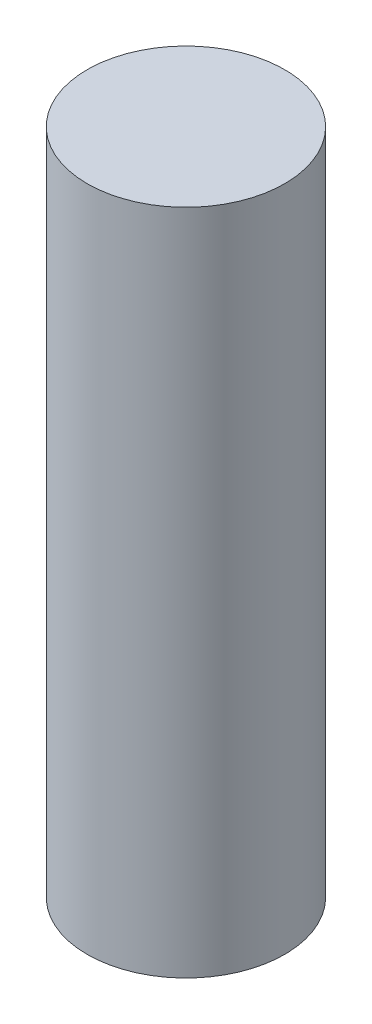
SolidWorks part; units mm, degrees
ref_plane "Front Plane" through (0, 0, 0) normal (0, 0, 1) x (1, 0, 0)
ref_plane "Top Plane" through (0, 0, 0) normal (0, 1, 0) x (1, 0, 0)
ref_plane "Right Plane" through (0, 0, 0) normal (1, 0, 0) x (0, 0, -1)
sketch "Sketch1" plane through (0, 0, 0) normal (0, 1, 0) x (1, 0, 0)
  circle A0 centre (0, 0) radius 14.8
  dimension "D1" = 29.6
extrude "Boss-Extrude1" add sketch "Sketch1" along normal blind 100
